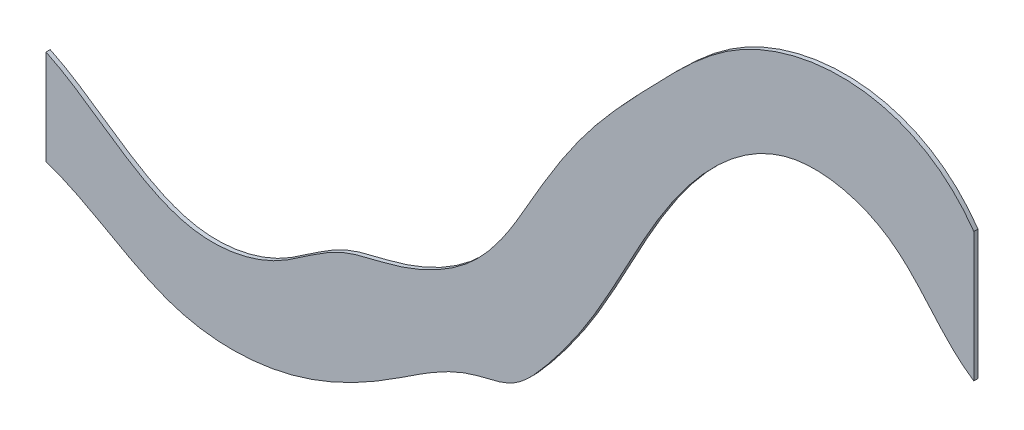
SolidWorks part; units mm, degrees
ref_plane "Front Plane" through (0, 0, 0) normal (0, 0, 1) x (1, 0, 0)
ref_plane "Top Plane" through (0, 0, 0) normal (0, 1, 0) x (1, 0, 0)
ref_plane "Right Plane" through (0, 0, 0) normal (1, 0, 0) x (0, 0, -1)
sketch "Sketch1" plane through (0, 0, 0) normal (0, 0, 1) x (1, 0, 0)
  line L0 (0, 7.874) -> (0, 18.1102)
  line L1 (100, 51.3601) -> (100, 37.4016)
  spline S0 degree 3 poles (0, 7.874) (4.9446, 6.2439) (10.4758, 1.5602) (19.801, 0.0784) (28.0456, 1.0231) (36.9054, 5.6248) (44.0023, 10.934) (50.4227, 11.835) (54.5546, 16.3692) (59.4752, 23.2282) (64.1435, 32.715) (70.2597, 42.4494) (79.6499, 50.1463) (92.6826, 46.9489) (96.4461, 39.7132) (100, 37.4016) knots 0 0 0 0 0.124881 0.163042 0.222969 0.319803 0.39841 0.431158 0.46893 0.538577 0.635461 0.718984 0.816425 0.900124 1 1 1 1
  spline S1 degree 3 poles (0, 18.1102) (5.1973, 15.6811) (12.5012, 7.7449) (25.0979, 10.2326) (30.8311, 15.6468) (38.8396, 16.9234) (47.53, 21.4372) (52.5951, 31.302) (58.5356, 40.5274) (65.918, 48.2338) (77.6815, 60.2702) (93.8349, 60.2243) (100, 51.3601) knots 0 0 0 0 0.148942 0.220352 0.28772 0.334218 0.414249 0.515237 0.595839 0.681769 0.774601 1 1 1 1
extrude "Boss-Extrude1" add sketch "Sketch1" along normal blind 0.45
scale "Scale2" scale about origin uniform scaling yes scale factor 7
